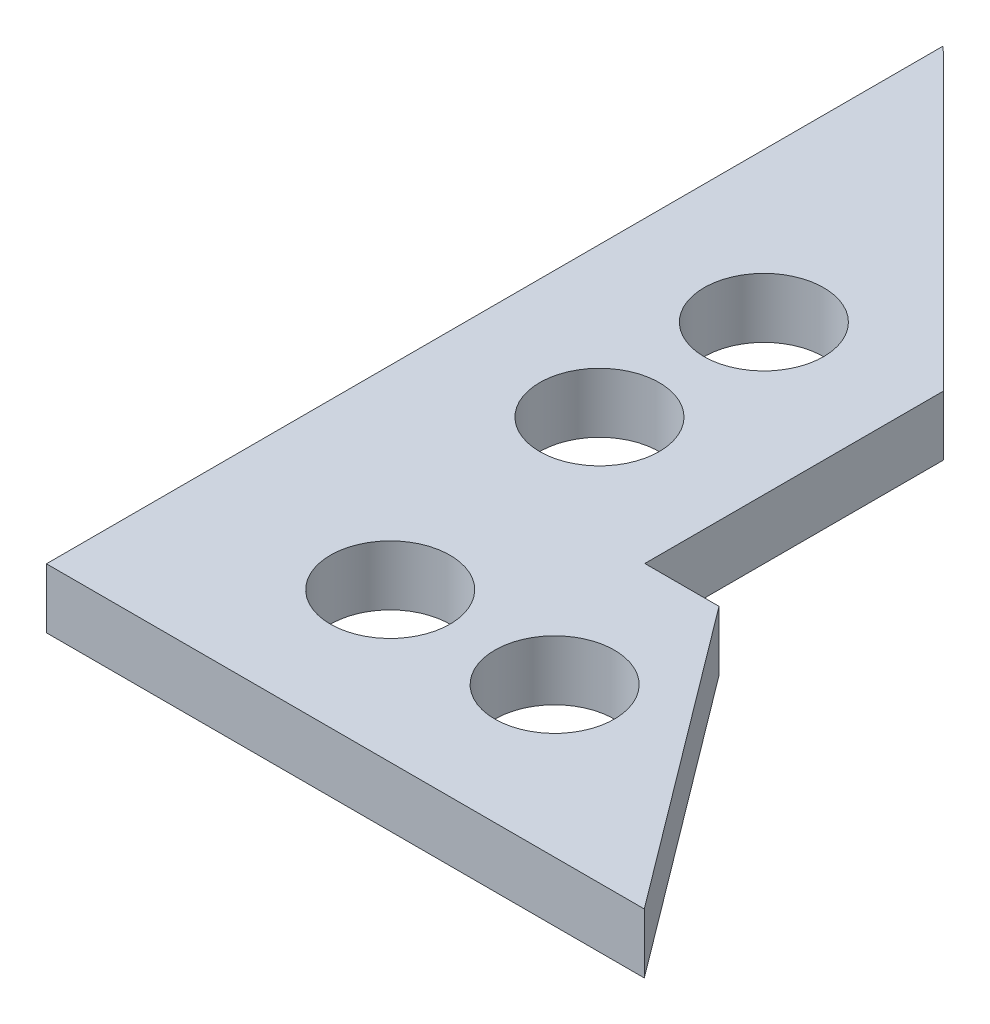
SolidWorks part; units mm, degrees
ref_plane "Front Plane" through (0, 0, 0) normal (0, 0, 1) x (1, 0, 0)
ref_plane "Top Plane" through (0, 0, 0) normal (0, 1, 0) x (1, 0, 0)
ref_plane "Right Plane" through (0, 0, 0) normal (1, 0, 0) x (0, 0, -1)
sketch "Sketch1" plane through (0, 0, 0) normal (0, 1, 0) x (1, 0, 0)
  line L0 (0, 0) -> (0, 76.2)
  line L1 (0, 0) -> (50.8, 0)
  line L2 (50.8, 0) -> (31.7048, 25.443)
  line L3 (25.4, 25.443) -> (31.7048, 25.443)
  line L4 (25.4, 25.443) -> (25.4, 50.8278)
  line L5 (25.4, 50.8278) -> (0, 76.2)
  dimension "D1" = 76.2
  dimension "D2" = 50.8
extrude "Boss-Extrude1" add sketch "Sketch1" along normal blind 5.08
sketch "Sketch2" plane through (0, 5.08, 0) normal (0, 1, 0) x (1, 0, 0)
  line L0 (0, 0) -> (50.8, 0) construction
  line L1 (0, 76.2) -> (0, 0) construction
  circle A0 centre (12.7, 34.29) radius 5.08
  circle A1 centre (12.7, 48.26) radius 5.08
  circle A2 centre (16.51, 12.7) radius 5.08
  circle A3 centre (30.48, 12.7) radius 5.08
  point P12 (0, 0)
  point P13 (0, 0)
  point P14 (0, 0)
  point P15 (0, 0)
  point P16 (0, 0)
  dimension "D1" = 34.29
  dimension "D2" = 48.26
  dimension "D3" = 16.51
  dimension "D4" = 30.48
  dimension "D5" = 12.7
  dimension "D6" = 12.7
extrude "Cut-Extrude1" cut sketch "Sketch2" against normal blind 7.62
